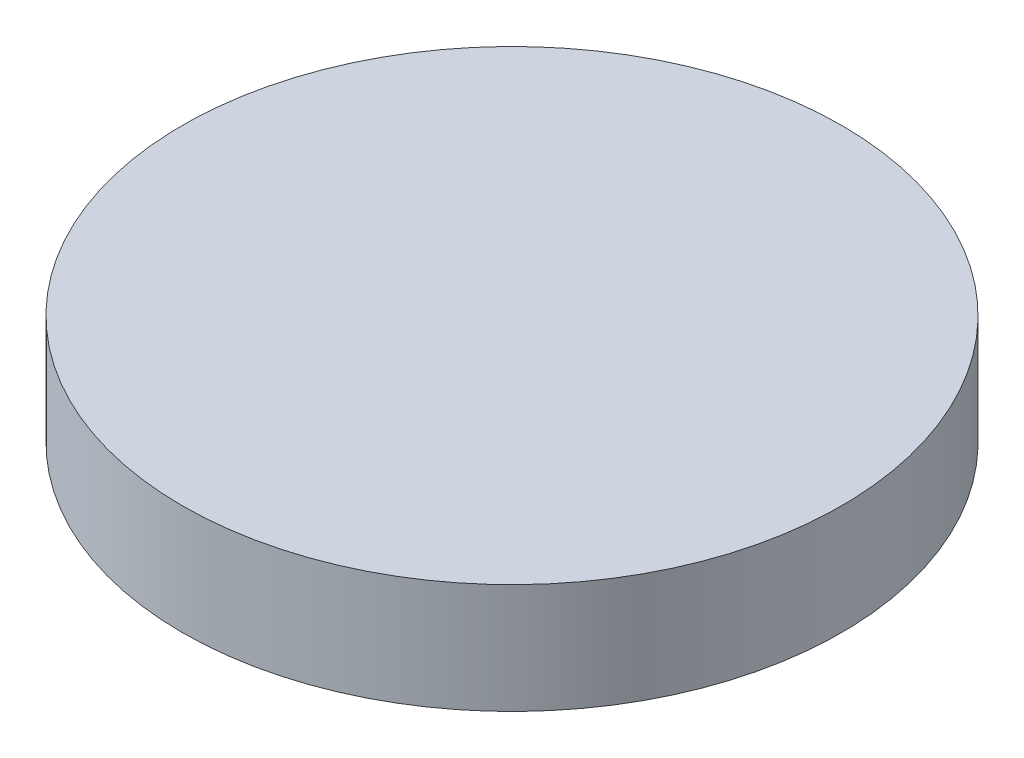
SolidWorks part; units mm, degrees
ref_plane "Front Plane" through (0, 0, 0) normal (0, 0, 1) x (1, 0, 0)
ref_plane "Top Plane" through (0, 0, 0) normal (0, 1, 0) x (1, 0, 0)
ref_plane "Right Plane" through (0, 0, 0) normal (1, 0, 0) x (0, 0, -1)
sketch "Sketch1" plane through (0, 0, 0) normal (0, 1, 0) x (1, 0, 0)
  circle A1 centre (0, 0) radius 1.5
  dimension "D1" = 3
extrude "Boss-Extrude1" add sketch "Sketch1" along normal blind 0.5
